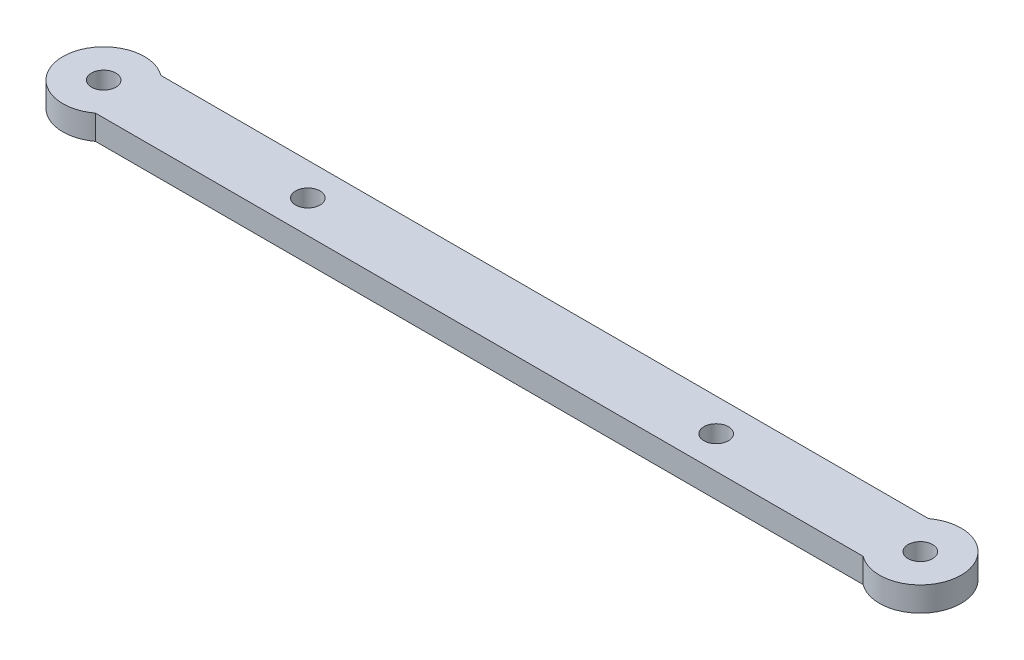
SolidWorks part; units mm, degrees
ref_plane "Alzado" through (0, 0, 0) normal (0, 0, 1) x (1, 0, 0)
ref_plane "Planta" through (0, 0, 0) normal (0, 1, 0) x (1, 0, 0)
ref_plane "Vista lateral" through (0, 0, 0) normal (1, 0, 0) x (0, 0, -1)
sketch "Croquis1" plane through (0, 0, 0) normal (0, 1, 0) x (1, 0, 0)
  line L0 (-47, 4) -> (47, 4)
  line L3 (47, -4) -> (-47, -4)
  circle A0 centre (-50, 0) radius 1.5
  arc A1 (-47, 4) -> (-47, -4) centre (-50, 0) ccw
  circle A2 centre (50, 0) radius 1.5
  arc A3 (47, 4) -> (47, -4) centre (50, 0) cw
  circle A4 centre (25, 0) radius 1.5
  circle A5 centre (-25, 0) radius 1.5
  dimension "D1" = 3
  dimension "D2" = 5
  dimension "D6" = 5
  dimension "D9" = 3
  dimension "D8" = 3
  dimension "D10" = 3
  dimension "D3" = 4
  dimension "D4" = 4
  dimension "D5" = 100
  dimension "D7" = 50
  dimension "D11" = 25
  dimension "D12" = 25
extrude "Saliente-Extruir1" add sketch "Croquis1" along normal blind 3
